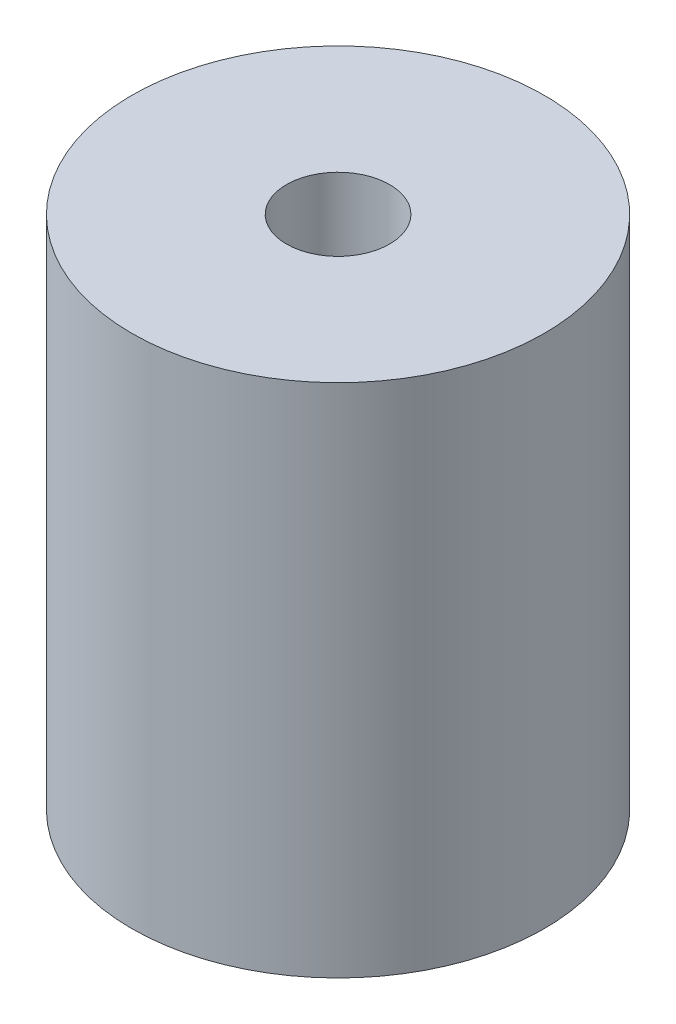
SolidWorks part; units mm, degrees
ref_plane "Front Plane" through (0, 0, 0) normal (0, 0, 1) x (1, 0, 0)
ref_plane "Top Plane" through (0, 0, 0) normal (0, 1, 0) x (1, 0, 0)
ref_plane "Right Plane" through (0, 0, 0) normal (1, 0, 0) x (0, 0, -1)
sketch "Sketch1" plane through (0, 0, 0) normal (0, 1, 0) x (1, 0, 0)
  circle A0 centre (0, 0) radius 10
  dimension "D1" = 20
extrude "Boss-Extrude1" add sketch "Sketch1" along normal mid plane 25
sketch "Sketch2" plane through (0, 0, 0) normal (0, 1, 0) x (1, 0, 0)
  circle A0 centre (0, 0) radius 2.5
  dimension "D1" = 5
extrude "Cut-Extrude1" cut sketch "Sketch2" along normal through all
sketch "Sketch3" plane through (0, -12.5, 0) normal (0, -1, 0) x (1, 0, 0)
  circle A0 centre (0, 0) radius 4
  dimension "D1" = 8
extrude "Cut-Extrude2" cut sketch "Sketch3" against normal up to surface (12.5 mm away) up to face at (0, 0, 2.5)
